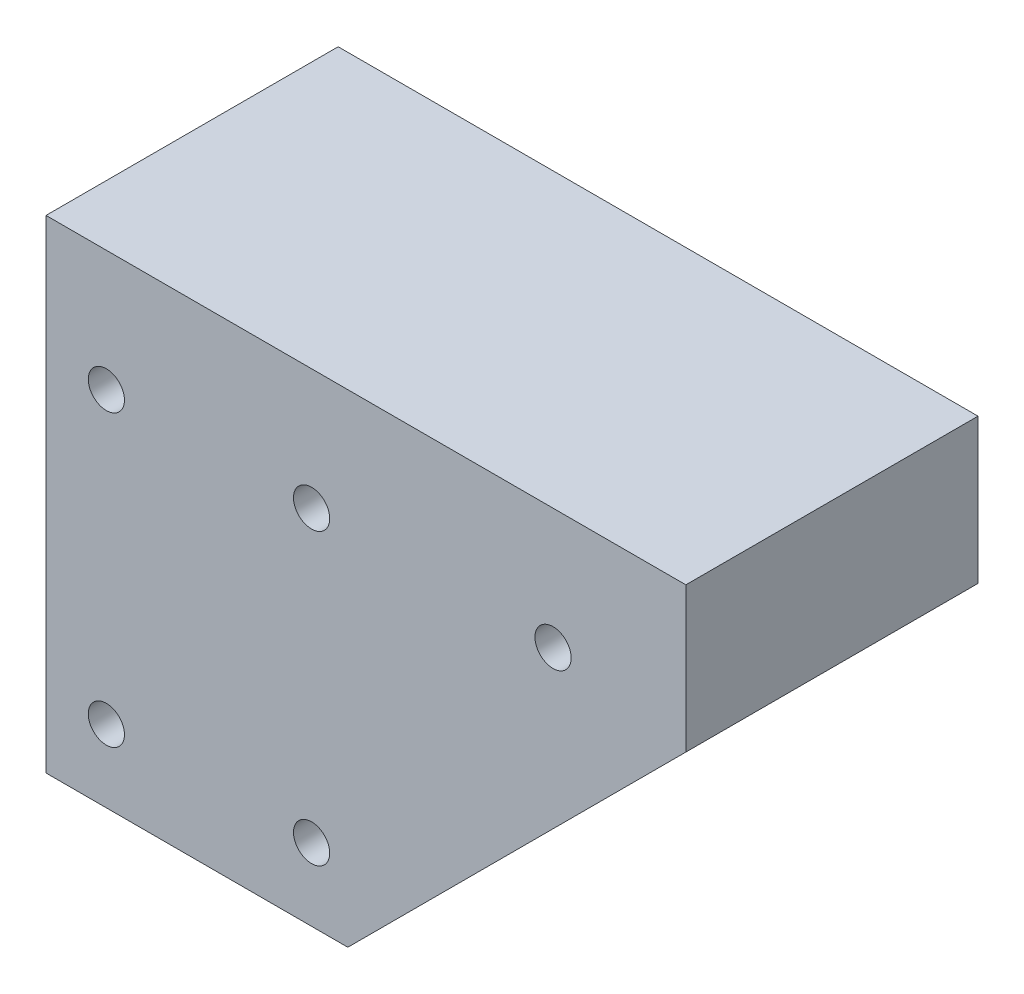
SolidWorks part; units mm, degrees
ref_plane "前视基准面" through (0, 0, 0) normal (0, 0, 1) x (1, 0, 0)
ref_plane "上视基准面" through (0, 0, 0) normal (0, 1, 0) x (1, 0, 0)
ref_plane "右视基准面" through (0, 0, 0) normal (1, 0, 0) x (0, 0, -1)
other "Configuration Table"
sketch "草图1" plane through (0, 0, 0) normal (0, 0, 1) x (1, 0, 0)
  line L1 (0, 0) -> (53, 0)
  line L2 (0, 0) -> (0, 40)
  line L3 (0, 40) -> (53, 40)
  line L4 (53, 0) -> (53, 40)
  dimension "D1" = 53
  dimension "D2" = 40
extrude "凸台-拉伸1" add sketch "草图1" along normal blind 24.2
sketch "草图2" plane through (0, 0, 24.2) normal (0, 0, 1) x (1, 0, 0)
  line L0 (53, 28) -> (53, 0)
  line L1 (53, 0) -> (53, 40) construction
  line L2 (53, 0) -> (25, 0)
  line L3 (0, 0) -> (53, 0) construction
  line L4 (25, 0) -> (53, 28)
  dimension "D1" = 28
  dimension "D2" = 28
extrude "切除-拉伸1" cut sketch "草图2" against normal through all
sketch "草图3" plane through (0, 0, 24.2) normal (0, 0, 1) x (1, 0, 0)
  line L0 (53, 40) -> (0, 40) construction
  line L1 (0, 40) -> (0, 0) construction
  circle A0 centre (5, 30) radius 1.5
  circle A1 centre (5, 6) radius 1.5
  circle A2 centre (22, 30) radius 1.5
  circle A3 centre (22, 6) radius 1.5
  circle A4 centre (42, 30) radius 1.5
  dimension "D1" = 3
  dimension "D2" = 10
  dimension "D3" = 5
  dimension "D4" = 17
  dimension "D5" = 24
  dimension "D6" = 20
extrude "切除-拉伸2" cut sketch "草图3" against normal through all
